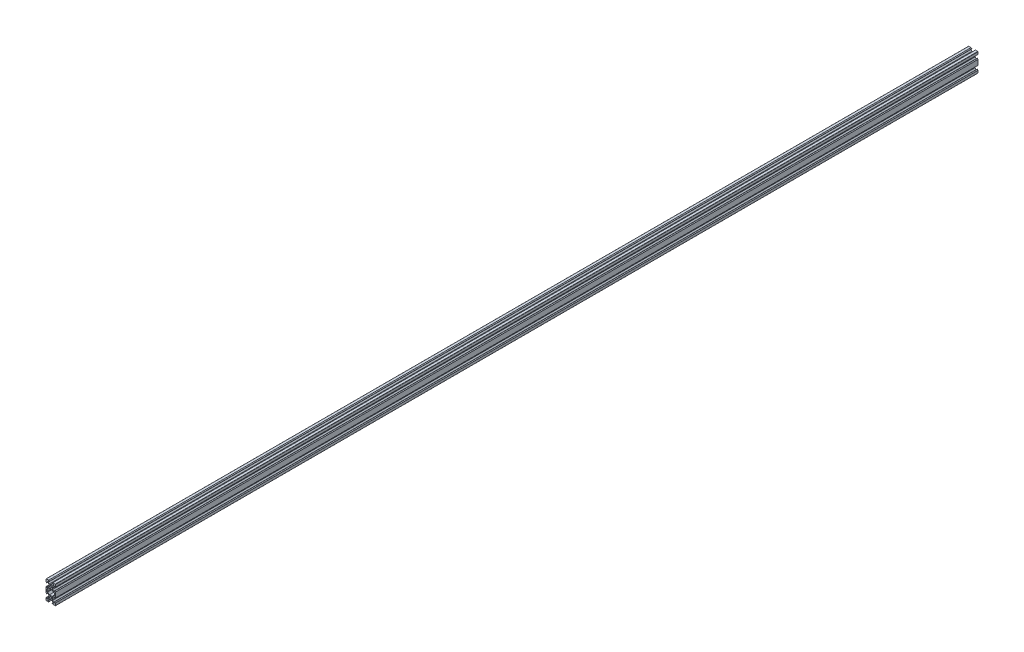
SolidWorks part; units mm, degrees
material "Aluminium"
ref_plane "Front Plane" through (0, 0, 0) normal (0, 0, 1) x (1, 0, 0)
ref_plane "Top Plane" through (0, 0, 0) normal (0, 1, 0) x (1, 0, 0)
ref_plane "Right Plane" through (0, 0, 0) normal (1, 0, 0) x (0, 0, -1)
sketch "Sketch1" plane through (0, 0, 0) normal (0, 0, 1) x (1, 0, 0)
  line L0 (0, 0) -> (10, 0) construction
  line L1 (9.5, -20) -> (-9.5, -20)
  line L2 (10, -19.5) -> (10, 19.5)
  line L3 (9.5, 20) -> (-9.5, 20)
  line L4 (-10, -19.5) -> (-10, 19.5)
  line L5 (10, -20) -> (-10, 20) construction
  line L6 (10, 20) -> (-10, -20) construction
  circle A0 centre (0, 10) radius 2.1
  circle A1 centre (0, -10) radius 2.1
  arc A2 (-9.5, -20) -> (-10, -19.5) centre (-9.5, -19.5) cw
  arc A3 (9.5, -20) -> (10, -19.5) centre (9.5, -19.5) ccw
  arc A4 (10, 19.5) -> (9.5, 20) centre (9.5, 19.5) ccw
  arc A5 (-9.5, 20) -> (-10, 19.5) centre (-9.5, 19.5) ccw
  point P0 (0, 0)
  line B0 (0, 10) -> (0, 20) construction
  line B1 (0, 13.69) -> (-0.21, 13.9)
  line B2 (-0.21, 13.9) -> (-2.8393, 13.9)
  line B3 (-2.8393, 13.9) -> (-5.5, 16.5607)
  line B4 (-5.5, 16.5607) -> (-5.5, 18.2)
  line B5 (-5.5, 18.2) -> (-3.125, 18.2)
  line B6 (-3.125, 18.2) -> (-3.125, 18.545)
  line B7 (-3.125, 18.545) -> (-4.58, 20)
  line B8 (-4.58, 20) -> (4.58, 20)
  line B9 (0, 10) -> (-5.9132, 15.9132) construction
  line B10 (3.125, 18.545) -> (4.58, 20)
  line B11 (3.125, 18.2) -> (3.125, 18.545)
  line B12 (5.5, 18.2) -> (3.125, 18.2)
  line B13 (5.5, 16.5607) -> (5.5, 18.2)
  line B14 (2.8393, 13.9) -> (5.5, 16.5607)
  line B15 (0.21, 13.9) -> (2.8393, 13.9)
  line B16 (0, 13.69) -> (0.21, 13.9)
  line B17 (0, 10) -> (-10, 10) construction
  line B18 (-3.69, 10) -> (-3.9, 9.79)
  line B19 (-3.9, 9.79) -> (-3.9, 7.1607)
  line B20 (-3.9, 7.1607) -> (-6.5607, 4.5)
  line B21 (-6.5607, 4.5) -> (-8.2, 4.5)
  line B22 (-8.2, 4.5) -> (-8.2, 6.875)
  line B23 (-8.2, 6.875) -> (-8.545, 6.875)
  line B24 (-8.545, 6.875) -> (-10, 5.42)
  line B25 (-10, 5.42) -> (-10, 14.58)
  line B26 (0, 10) -> (-5.9132, 4.0868) construction
  line B27 (-8.545, 13.125) -> (-10, 14.58)
  line B28 (-8.2, 13.125) -> (-8.545, 13.125)
  line B29 (-8.2, 15.5) -> (-8.2, 13.125)
  line B30 (-6.5607, 15.5) -> (-8.2, 15.5)
  line B31 (-3.9, 12.8393) -> (-6.5607, 15.5)
  line B32 (-3.9, 10.21) -> (-3.9, 12.8393)
  line B33 (-3.69, 10) -> (-3.9, 10.21)
  line B34 (0, -10) -> (-10, -10) construction
  line B35 (-3.69, -10) -> (-3.9, -10.21)
  line B36 (-3.9, -10.21) -> (-3.9, -12.8393)
  line B37 (-3.9, -12.8393) -> (-6.5607, -15.5)
  line B38 (-6.5607, -15.5) -> (-8.2, -15.5)
  line B39 (-8.2, -15.5) -> (-8.2, -13.125)
  line B40 (-8.2, -13.125) -> (-8.545, -13.125)
  line B41 (-8.545, -13.125) -> (-10, -14.58)
  line B42 (-10, -14.58) -> (-10, -5.42)
  line B43 (0, -10) -> (-5.9132, -15.9132) construction
  line B44 (-8.545, -6.875) -> (-10, -5.42)
  line B45 (-8.2, -6.875) -> (-8.545, -6.875)
  line B46 (-8.2, -4.5) -> (-8.2, -6.875)
  line B47 (-6.5607, -4.5) -> (-8.2, -4.5)
  line B48 (-3.9, -7.1607) -> (-6.5607, -4.5)
  line B49 (-3.9, -9.79) -> (-3.9, -7.1607)
  line B50 (-3.69, -10) -> (-3.9, -9.79)
  line B51 (0, -10) -> (0, -20) construction
  line B52 (0, -13.69) -> (0.21, -13.9)
  line B53 (0.21, -13.9) -> (2.8393, -13.9)
  line B54 (2.8393, -13.9) -> (5.5, -16.5607)
  line B55 (5.5, -16.5607) -> (5.5, -18.2)
  line B56 (5.5, -18.2) -> (3.125, -18.2)
  line B57 (3.125, -18.2) -> (3.125, -18.545)
  line B58 (3.125, -18.545) -> (4.58, -20)
  line B59 (4.58, -20) -> (-4.58, -20)
  line B60 (0, -10) -> (5.9132, -15.9132) construction
  line B61 (-3.125, -18.545) -> (-4.58, -20)
  line B62 (-3.125, -18.2) -> (-3.125, -18.545)
  line B63 (-5.5, -18.2) -> (-3.125, -18.2)
  line B64 (-5.5, -16.5607) -> (-5.5, -18.2)
  line B65 (-2.8393, -13.9) -> (-5.5, -16.5607)
  line B66 (-0.21, -13.9) -> (-2.8393, -13.9)
  line B67 (0, -13.69) -> (-0.21, -13.9)
  line B68 (0, -10) -> (10, -10) construction
  line B69 (3.69, -10) -> (3.9, -9.79)
  line B70 (3.9, -9.79) -> (3.9, -7.1607)
  line B71 (3.9, -7.1607) -> (6.5607, -4.5)
  line B72 (6.5607, -4.5) -> (8.2, -4.5)
  line B73 (8.2, -4.5) -> (8.2, -6.875)
  line B74 (8.2, -6.875) -> (8.545, -6.875)
  line B75 (8.545, -6.875) -> (10, -5.42)
  line B76 (10, -5.42) -> (10, -14.58)
  line B77 (0, -10) -> (5.9132, -4.0868) construction
  line B78 (8.545, -13.125) -> (10, -14.58)
  line B79 (8.2, -13.125) -> (8.545, -13.125)
  line B80 (8.2, -15.5) -> (8.2, -13.125)
  line B81 (6.5607, -15.5) -> (8.2, -15.5)
  line B82 (3.9, -12.8393) -> (6.5607, -15.5)
  line B83 (3.9, -10.21) -> (3.9, -12.8393)
  line B84 (3.69, -10) -> (3.9, -10.21)
  line B85 (0, 10) -> (10, 10) construction
  line B86 (3.69, 10) -> (3.9, 10.21)
  line B87 (3.9, 10.21) -> (3.9, 12.8393)
  line B88 (3.9, 12.8393) -> (6.5607, 15.5)
  line B89 (6.5607, 15.5) -> (8.2, 15.5)
  line B90 (8.2, 15.5) -> (8.2, 13.125)
  line B91 (8.2, 13.125) -> (8.545, 13.125)
  line B92 (8.545, 13.125) -> (10, 14.58)
  line B93 (10, 14.58) -> (10, 5.42)
  line B94 (0, 10) -> (5.9132, 15.9132) construction
  line B95 (8.545, 6.875) -> (10, 5.42)
  line B96 (8.2, 6.875) -> (8.545, 6.875)
  line B97 (8.2, 4.5) -> (8.2, 6.875)
  line B98 (6.5607, 4.5) -> (8.2, 4.5)
  line B99 (3.9, 7.1607) -> (6.5607, 4.5)
  line B100 (3.9, 9.79) -> (3.9, 7.1607)
  line B101 (3.69, 10) -> (3.9, 9.79)
  line B102 (-8.2, -2.7) -> (-8.2, 2.7)
  line B103 (-8.2, 2.7) -> (-6.2393, 2.7)
  line B104 (-6.2393, 2.7) -> (-2.8393, 6.1)
  line B105 (-2.8393, 6.1) -> (2.8393, 6.1)
  line B106 (0, 6.1) -> (0, 0) construction
  line B107 (0, 0) -> (-8.2, 0) construction
  line B108 (6.2393, 2.7) -> (2.8393, 6.1)
  line B109 (8.2, 2.7) -> (6.2393, 2.7)
  line B110 (8.2, -2.7) -> (8.2, 2.7)
  line B111 (8.2, -2.7) -> (6.2393, -2.7)
  line B112 (6.2393, -2.7) -> (2.8393, -6.1)
  line B113 (-2.8393, -6.1) -> (2.8393, -6.1)
  line B114 (-6.2393, -2.7) -> (-2.8393, -6.1)
  line B115 (-8.2, -2.7) -> (-6.2393, -2.7)
  line B116 (0, 6.1) -> (0, 10) construction
  line B117 (0, 10) -> (-5.0927, 4.9073) construction
  dimension "D4" = 4.2
  dimension "D5" = 0.5
  dimension "D1" = 20
  dimension "D2" = 40
  dimension "D3" = 20
sketch_block_instance "V Slot 1-4"
sketch_block "V Slot 1" parameters "D1"=10, "D2"=11, "D3"=4.3, "D4"=1.8, "D5"=0.21, "D6"=45, "D7"=9.16, "D8"=1.5, "D9"=6.25
sketch_block_instance "V Slot 1-5"
sketch_block_instance "V Slot 1-6"
sketch_block_instance "V Slot 1-7"
sketch_block_instance "V Slot 1-8"
sketch_block_instance "V Slot 1-9"
sketch_block_instance "Center Cutout 1-1"
sketch_block "Center Cutout 1" parameters "D1"=5.4, "D2"=12.2, "D3"=8.2, "D4"=45, "D5"=10, "D6"=1.5
extrude "Boss-Extrude1" add sketch "Sketch1" along normal mid plane 1960 contours B101 B86 B87 B88 B89 B90 B91 B92 L2 A4 L3 B10 B11 B12 B13 B14 B15 B16 B1 B2 B3 B4 B5 B6 B7 A5 L4 B27 B28 B29 B30 B31 B32 B33 B18 B19 B20 B21 B22 B23 B24 B44 B45 B46 B47 B48 B49 B50 B35
